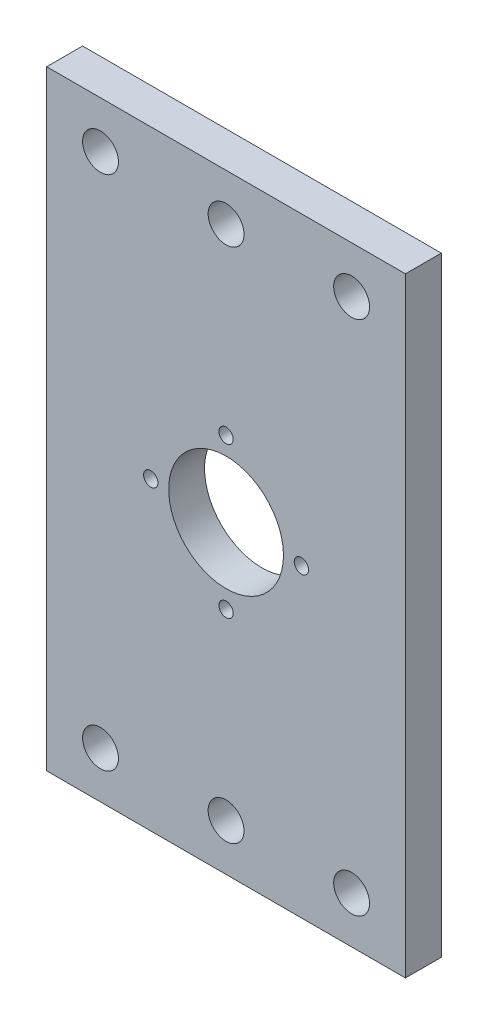
SolidWorks part; units mm, degrees
material "1060 合金"
ref_plane "前视基准面" through (0, 0, 0) normal (0, 0, 1) x (1, 0, 0)
ref_plane "上视基准面" through (0, 0, 0) normal (0, 1, 0) x (1, 0, 0)
ref_plane "右视基准面" through (0, 0, 0) normal (1, 0, 0) x (0, 0, -1)
sketch "草图1" plane through (0, 0, 0) normal (0, 0, 1) x (1, 0, 0)
  line L5 (50, -85) -> (-50, -85)
  line L9 (50, 85) -> (-50, 85)
  line L14 (50, 0) -> (50, -85)
  line L15 (-50, -85) -> (-50, -40)
  line L18 (50, 0) -> (50, 85)
  line L19 (-50, -40) -> (-50, 85)
  dimension "D1" = 85
  dimension "D2" = 85
  dimension "D3" = 0
  dimension "D4" = 100
  dimension "D5" = 50
extrude "凸台-拉伸1" add sketch "草图1" along normal blind 10 contours L9 L19 L15 L5 L14 L18
sketch "草图2" plane through (0, 0, 10) normal (0, 0, 1) x (1, 0, 0)
  circle A0 centre (0, 0) radius 16
extrude "切除-拉伸1" cut sketch "草图2" against normal blind 10
sketch "草图3" plane through (0, 0, 10) normal (0, 0, 1) x (1, 0, 0)
  circle A0 centre (0, -72) radius 5
  circle A1 centre (35, -72) radius 5
  circle A2 centre (-35, -72) radius 5
  dimension "D1" = 72
  dimension "D2" = 72
  dimension "D3" = 72
  dimension "D4" = 35
  dimension "D5" = 35
  dimension "D6" = 0
extrude "切除-拉伸2" cut sketch "草图3" against normal blind 10
sketch "草图6" plane through (0, 0, 10) normal (0, 0, 1) x (1, 0, 0)
  circle A0 centre (0, 21) radius 2
extrude "切除-拉伸4" cut sketch "草图6" against normal blind 10
pattern_circular "阵列(圆周)1" count 4 over 360 about axis through (0, 0, 0) along (0, 0, 1) of "切除-拉伸4"
mirror "镜向1" about plane through (0, 0, 0) normal (0, 1, 0) of "切除-拉伸2"
fillet "圆角1" [suppressed] radius 0.5
